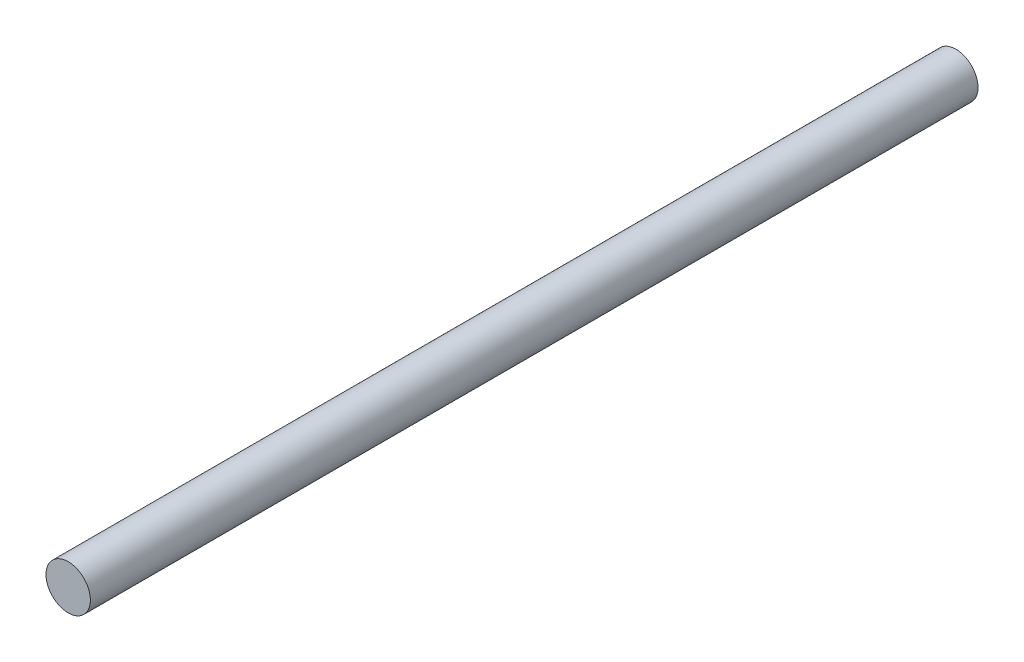
SolidWorks part; units mm, degrees
ref_plane "Front Plane" through (0, 0, 0) normal (0, 0, 1) x (1, 0, 0)
ref_plane "Top Plane" through (0, 0, 0) normal (0, 1, 0) x (1, 0, 0)
ref_plane "Right Plane" through (0, 0, 0) normal (1, 0, 0) x (0, 0, -1)
sketch "Sketch1" plane through (0, 0, 0) normal (0, 0, 1) x (1, 0, 0)
  circle A0 centre (0, 0) radius 1.905
  dimension "D1" = 3.81
extrude "Boss-Extrude1" add sketch "Sketch1" along normal blind 76.2
